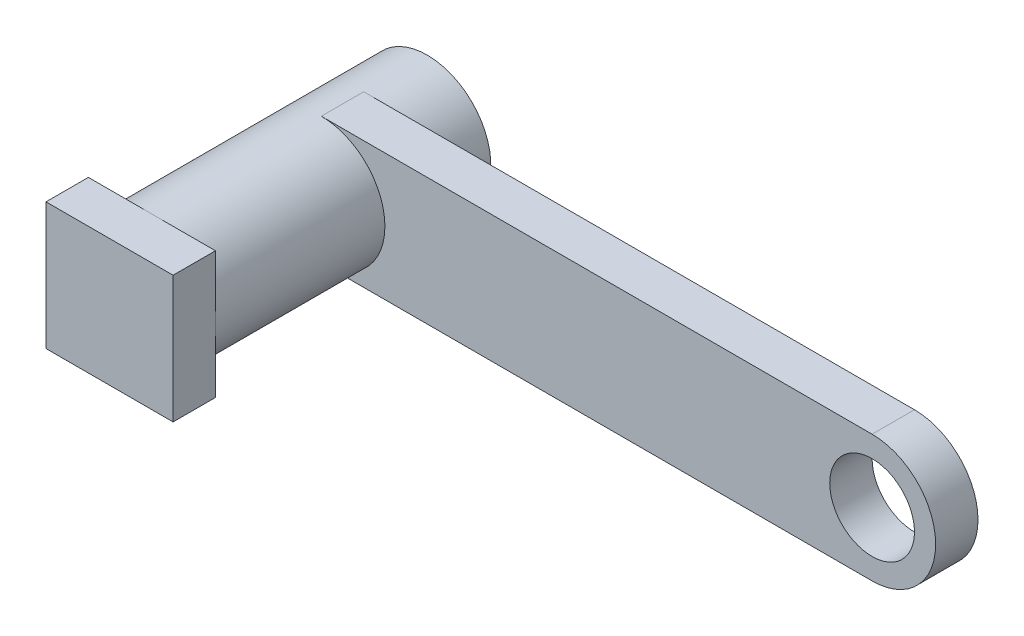
SolidWorks part; units mm, degrees
ref_plane "Alzado" through (0, 0, 0) normal (0, 0, 1) x (1, 0, 0)
ref_plane "Planta" through (0, 0, 0) normal (0, 1, 0) x (1, 0, 0)
ref_plane "Vista lateral" through (0, 0, 0) normal (1, 0, 0) x (0, 0, -1)
sketch "Croquis1" plane through (0, 0, 0) normal (0, 0, 1) x (1, 0, 0)
  line L4 (20.7075, 22.5) -> (20.7075, -7.5) construction
  line L5 (-44.2925, 22.5) -> (85.7075, 22.5)
  line L7 (-44.2925, -7.5) -> (85.7075, -7.5)
  arc A6 (-44.2925, 22.5) -> (-44.2925, -7.5) centre (-44.2925, 7.5) ccw
  circle A7 centre (-44.2925, 7.5) radius 10
  arc A8 (85.7075, 22.5) -> (85.7075, -7.5) centre (85.7075, 7.5) cw
  circle A9 centre (85.7075, 7.5) radius 10
  dimension "D3" = 130
  dimension "D1" = 20
  dimension "D2" = 30
extrude "Saliente-Extruir1" add sketch "Croquis1" along normal blind 10
sketch "Croquis2" plane through (0, 0, 10) normal (0, 0, 1) x (1, 0, 0)
  circle A0 centre (-44.2925, 7.5) radius 15
  circle A1 centre (-44.2925, 7.5) radius 10
extrude "Saliente-Extruir2" add sketch "Croquis2" along normal blind 40
sketch "Croquis3" plane through (0, 0, 50) normal (0, 0, 1) x (1, 0, 0)
  line L7 (-44.2925, -7.5) -> (85.7075, -7.5) construction
  line L8 (-59.2925, 22.5) -> (-29.2925, 22.5)
  line L9 (-59.2925, 22.5) -> (-59.2925, -7.5)
  line L10 (-59.2925, -7.5) -> (-29.2925, -7.5)
  line L11 (-29.2925, 22.5) -> (-29.2925, -7.5)
  circle A1 centre (-44.2925, 7.5) radius 15 construction
extrude "Saliente-Extruir3" add sketch "Croquis3" along normal blind 10
sketch "Sketch1" plane through (0, 0, 0) normal (0, 0, -1) x (-1, 0, 0)
  circle A0 centre (44.2925, 7.5) radius 10
  circle A1 centre (44.2925, 7.5) radius 15
extrude "Boss-Extrude1" add sketch "Sketch1" along normal blind 15
